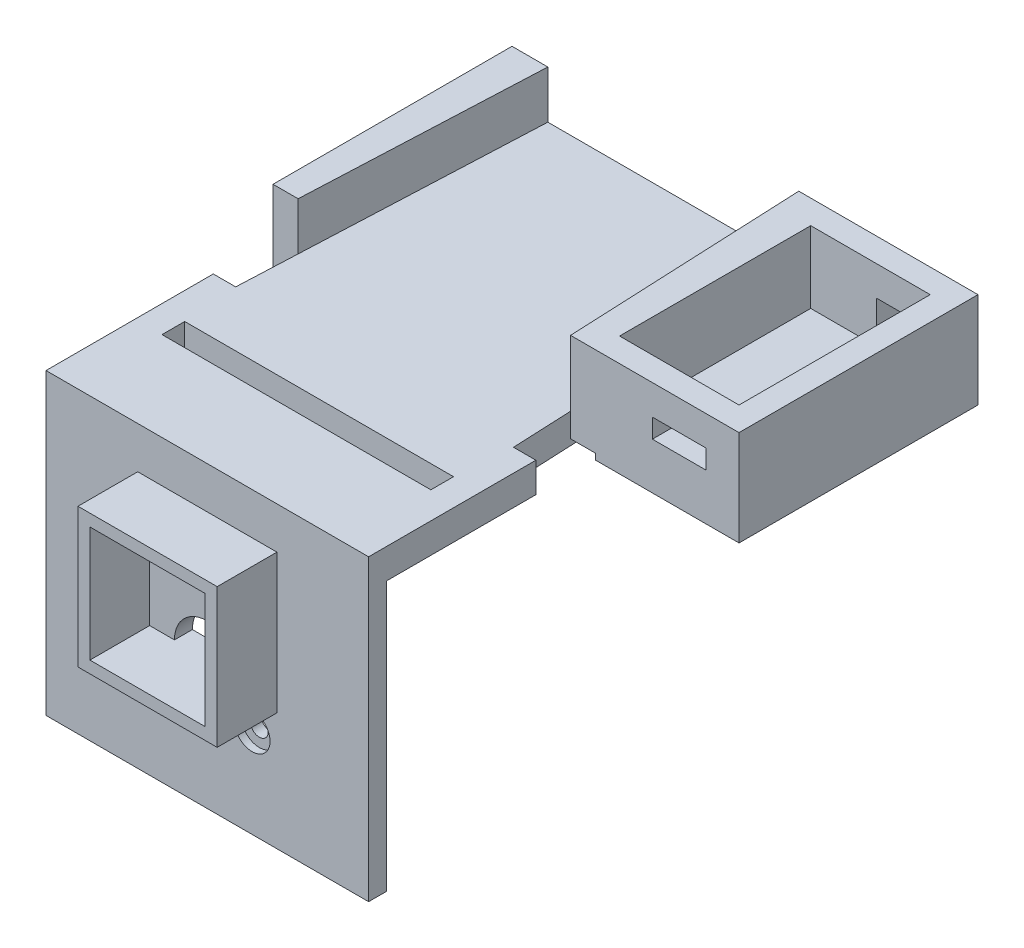
SolidWorks part; units mm, degrees
ref_plane "Alzado" through (0, 0, 0) normal (0, 0, 1) x (1, 0, 0)
ref_plane "Planta" through (0, 0, 0) normal (0, 1, 0) x (1, 0, 0)
ref_plane "Vista lateral" through (0, 0, 0) normal (1, 0, 0) x (0, 0, -1)
sketch "Croquis1" plane through (0, 0, 0) normal (0, 0, 1) x (1, 0, 0)
  line L0 (27, 35) -> (-27, 35)
  line L1 (-27, 35) -> (-27, -35)
  line L2 (0, 0) -> (-19.7131, 0) construction
  line L3 (0, 0) -> (0, 24.5917) construction
  line L4 (27, 35) -> (27, -35)
  line L5 (27, -35) -> (-27, -35)
  circle A1 centre (-7.5, 0) radius 1.5
  circle A2 centre (7.5, 0) radius 1.5
  point P12 (0, 35)
  point P13 (27, 0)
  point P14 (-27, 0)
  dimension "D3" = 7.5
  dimension "D4" = 3
  dimension "D1" = 27
  dimension "D2" = 35
extrude "Saliente-Extruir1" add sketch "Croquis1" along normal blind 3
sketch "Croquis2" plane through (0, 0, 3) normal (0, 0, 1) x (1, 0, 0)
  line L0 (0, 0) -> (-7.5, 0) construction
  line L1 (0, 0) -> (0, 12.2683) construction
  circle A0 centre (-7.5, 0) radius 3
  circle A1 centre (7.5, 0) radius 3
  dimension "D2" = 6
  dimension "D1" = 7.5
extrude "Cortar-Extruir1" cut sketch "Croquis2" against normal blind 1.2
sketch "Croquis3" plane through (0, 0, 3) normal (0, 0, 1) x (1, 0, 0)
  line L0 (0, 0) -> (0, 25.9775) construction
  line L1 (-9.65, 26) -> (-9.65, 6.7)
  line L2 (-9.65, 6.7) -> (9.65, 6.7)
  line L3 (-9.65, 26) -> (9.65, 26)
  line L4 (11.65, 28) -> (-11.65, 28)
  line L5 (-11.65, 28) -> (-11.65, 4.7)
  line L6 (-11.65, 4.7) -> (11.65, 4.7)
  line L7 (27, 35) -> (-27, 35) construction
  line L8 (11.65, 28) -> (11.65, 4.7)
  line L9 (9.65, 26) -> (9.65, 6.7)
  point P7 (0, 28)
  point P14 (0, 4.7)
  point P15 (0, 6.7)
  point P17 (0, 26)
  dimension "D1" = 19.3
  dimension "D2" = 9.65
  dimension "D3" = 2
  dimension "D4" = 2
  dimension "D5" = 2
  dimension "D6" = 7
extrude "Saliente-Extruir2" add sketch "Croquis3" along normal blind 10
sketch "Croquis4" plane through (0, 0, 0) normal (0, 0, -1) x (-1, 0, 0)
  line L0 (-27, 35) -> (-27, 30)
  line L1 (-27, -35) -> (-27, 35) construction
  line L2 (-27, 30) -> (27, 30)
  line L3 (27, 35) -> (27, -35) construction
  line L4 (27, 30) -> (27, 35)
  line L5 (27, 35) -> (-27, 35)
  dimension "D1" = 5
extrude "Saliente-Extruir3" add sketch "Croquis4" along normal blind 75
sketch "Croquis6" plane through (0, 0, 0) normal (0, 0, -1) x (-1, 0, 0)
  line L0 (0, 0) -> (0, -15) construction
  line L1 (-27, -15) -> (27, -15)
  line L2 (-27, -35) -> (-27, 30) construction
  line L3 (27, 30) -> (27, -35) construction
  line L4 (-27, -15) -> (-27, -35)
  line L5 (-27, -35) -> (27, -35)
  line L6 (27, -35) -> (27, -15)
  dimension "D1" = 15
extrude "Cortar-Extruir2" cut sketch "Croquis6" against normal up to surface (3 mm away) up to face at (0, 0, 3)
sketch "Croquis7" plane through (0, 35, 0) normal (0, 1, 0) x (1, 0, 0)
  line L0 (-27, 75) -> (-21, 75)
  line L1 (-27, 75) -> (27, 75) construction
  line L2 (-21, 75) -> (-23.25, 25)
  line L3 (-23.25, 25) -> (-27, 25)
  line L4 (-27, -3) -> (-27, 75) construction
  line L5 (-27, 25) -> (-27, 75)
  line L6 (0, 0) -> (0, 33.2519) construction
  line L7 (23.25, 25) -> (27, 25)
  line L8 (21, 75) -> (23.25, 25)
  line L9 (27, 75) -> (21, 75)
  line L10 (27, 25) -> (27, 75)
  dimension "D1" = 50
  dimension "D2" = 23.25
  dimension "D3" = 21
extrude "Cortar-Extruir4" cut sketch "Croquis7" against normal up to surface (5 mm away) up to face at (0, 30, -37.5)
sketch "Croquis8" plane through (0, 35, 0) normal (0, 1, 0) x (1, 0, 0)
  line L0 (22.5, 11.9169) -> (-22.5, 11.9169)
  line L1 (-22.5, 11.9169) -> (-22.5, 15.7169)
  line L2 (-22.5, 15.7169) -> (22.5, 15.7169)
  line L3 (0, 0) -> (0, 15.7169) construction
  line L4 (22.5, 11.9169) -> (22.5, 15.7169)
  point P7 (0, 11.9169)
  dimension "D1" = 3.8
  dimension "D2" = 22.5
extrude "Cortar-Extruir5" cut sketch "Croquis8" against normal up to surface (5 mm away) up to face at (0, 30, -31.25)
sketch "Croquis9" plane through (0, 0, 3) normal (0, 0, 1) x (1, 0, 0)
  line L0 (9.65, 26) -> (-0.85, 26)
  line L1 (9.65, 26) -> (-9.65, 26) construction
  line L2 (-0.85, 26) -> (-0.85, 22.3)
  line L3 (-0.85, 22.3) -> (9.65, 22.3)
  line L4 (9.65, 6.7) -> (9.65, 26) construction
  line L5 (9.65, 22.3) -> (9.65, 26)
  line L6 (-9.65, 6.7) -> (9.65, 6.7) construction
  line L7 (5.5, 6.7) -> (-5.5, 6.7)
  arc A0 (5.5, 6.7) -> (-5.5, 6.7) centre (0, 6.7) ccw
  dimension "D3" = 5.5
  dimension "D1" = 10.5
  dimension "D2" = 3.7
extrude "Cortar-Extruir6" cut sketch "Croquis9" against normal up to surface (3 mm away) up to face at (6, 0, 0)
sketch "Croquis10" plane through (0, 35, 0) normal (0, 1, 0) x (1, 0, 0)
  line L0 (-21, 75) -> (-27, 75)
  line L1 (-27, 75) -> (-27, 35)
  line L2 (-27, 35) -> (-22.8, 35)
  line L3 (-23.25, 25) -> (-21, 75) construction
  line L4 (-22.8, 35) -> (-21, 75)
  line L5 (0, 75) -> (0, 48.7673) construction
  line L6 (-21, 75) -> (21, 75) construction
  line L7 (27, 35) -> (22.8, 35)
  line L8 (27, 75) -> (27, 35)
  line L9 (21, 75) -> (27, 75)
  line L10 (22.8, 35) -> (21, 75)
  dimension "D1" = 40
  dimension "D2" = 6
extrude "Saliente-Extruir4" add sketch "Croquis10" along normal blind 8 and the other way blind 4
sketch "Croquis11" plane through (27, 0, 0) normal (1, 0, 0) x (0, 0, -1)
  line L0 (35, 43) -> (39, 43)
  line L1 (35, 43) -> (75, 43) construction
  line L2 (39, 43) -> (39, 34)
  line L3 (39, 34) -> (71, 34)
  line L4 (71, 34) -> (71, 43)
  line L5 (71, 43) -> (75, 43)
  line L6 (75, 43) -> (75, 30)
  line L7 (75, 30) -> (35, 30)
  line L8 (25, 30) -> (75, 30) construction
  line L9 (35, 30) -> (35, 43)
  dimension "D1" = 32
  dimension "D2" = 4
  dimension "D3" = 4
extrude "Saliente-Extruir5" add sketch "Croquis11" along normal blind 20
sketch "Croquis12" plane through (0, 0, -75) normal (0, 0, -1) x (-1, 0, 0)
  line L0 (-47, 34) -> (-38, 34)
  line L1 (-47, 30) -> (-47, 43) construction
  line L2 (-38, 34) -> (-38, 41)
  line L3 (-38, 41) -> (-47, 41)
  line L4 (-47, 41) -> (-47, 34)
  line L5 (-47, 30) -> (-27, 30) construction
  dimension "D1" = 4
  dimension "D2" = 9
  dimension "D3" = 7
extrude "Cortar-Extruir7" cut sketch "Croquis12" against normal up to surface (4 mm away) up to face at (37, 38.5, -71)
sketch "Croquis13" plane through (47, 0, 0) normal (1, 0, 0) x (0, 0, -1)
  line L0 (35, 43) -> (75, 43)
  line L1 (75, 43) -> (75, 30)
  line L2 (75, 30) -> (35, 30)
  line L3 (35, 30) -> (35, 43)
extrude "Saliente-Extruir6" add sketch "Croquis13" along normal blind 4
sketch "Croquis16" plane through (0, 0, -35) normal (0, 0, 1) x (1, 0, 0)
  line L0 (36.5, 41) -> (36.5, 37.8)
  line L1 (36.5, 37.8) -> (45.5, 37.8)
  line L2 (45.5, 37.8) -> (45.5, 41)
  line L3 (45.5, 41) -> (36.5, 41)
  line L4 (51, 30) -> (27, 30) construction
  line L5 (51, 43) -> (51, 30) construction
  dimension "D1" = 9
  dimension "D2" = 3.2
  dimension "D3" = 7.8
  dimension "D4" = 5.5
extrude "Cortar-Extruir9" cut sketch "Croquis16" against normal up to surface (4 mm away) up to face at (37, 38.5, -39)
sketch "Croquis17" plane through (0, 43, 0) normal (0, 1, 0) x (1, 0, 0)
  line L0 (21, 75) -> (51, 75)
  line L1 (51, 75) -> (51, 35)
  line L2 (51, 35) -> (22.8, 35)
  line L3 (22.8, 35) -> (21, 75)
  line L4 (27, 71) -> (27, 39)
  line L5 (27, 39) -> (27, 71) construction
  line L6 (27, 71) -> (27, 39) construction
  line L7 (27, 39) -> (47, 39)
  line L8 (47, 39) -> (27, 39) construction
  line L9 (47, 39) -> (27, 39) construction
  line L10 (47, 39) -> (47, 71)
  line L11 (47, 71) -> (27, 71)
extrude "Saliente-Extruir7" add sketch "Croquis17" along normal blind 3
